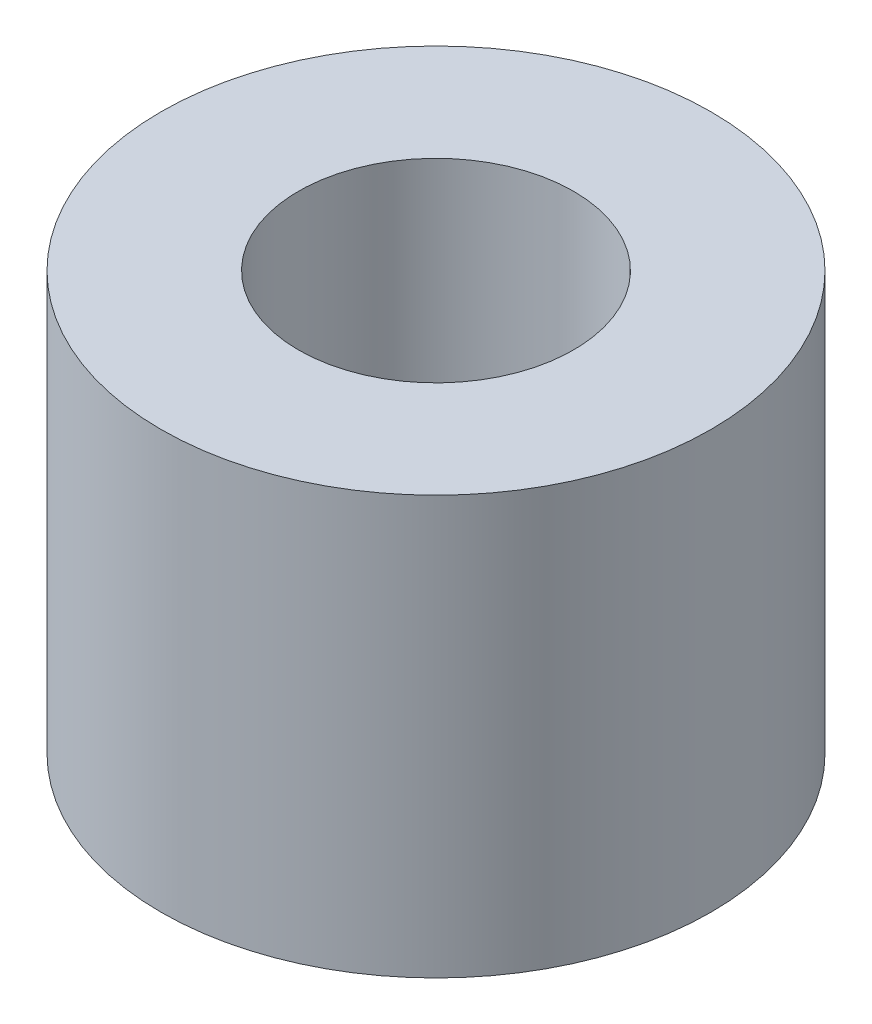
SolidWorks part; units mm, degrees
ref_plane "Front Plane" through (0, 0, 0) normal (0, 0, 1) x (1, 0, 0)
ref_plane "Top Plane" through (0, 0, 0) normal (0, 1, 0) x (1, 0, 0)
ref_plane "Right Plane" through (0, 0, 0) normal (1, 0, 0) x (0, 0, -1)
sketch "Sketch2" plane through (0, 0, 0) normal (0, 1, 0) x (1, 0, 0)
  circle A0 centre (0, 0) radius 6.35
  circle A1 centre (0, 0) radius 3.175
  dimension "D1" = 12.7
  dimension "D2" = 6.35
extrude "Boss-Extrude1" add sketch "Sketch2" along normal blind 9.652
